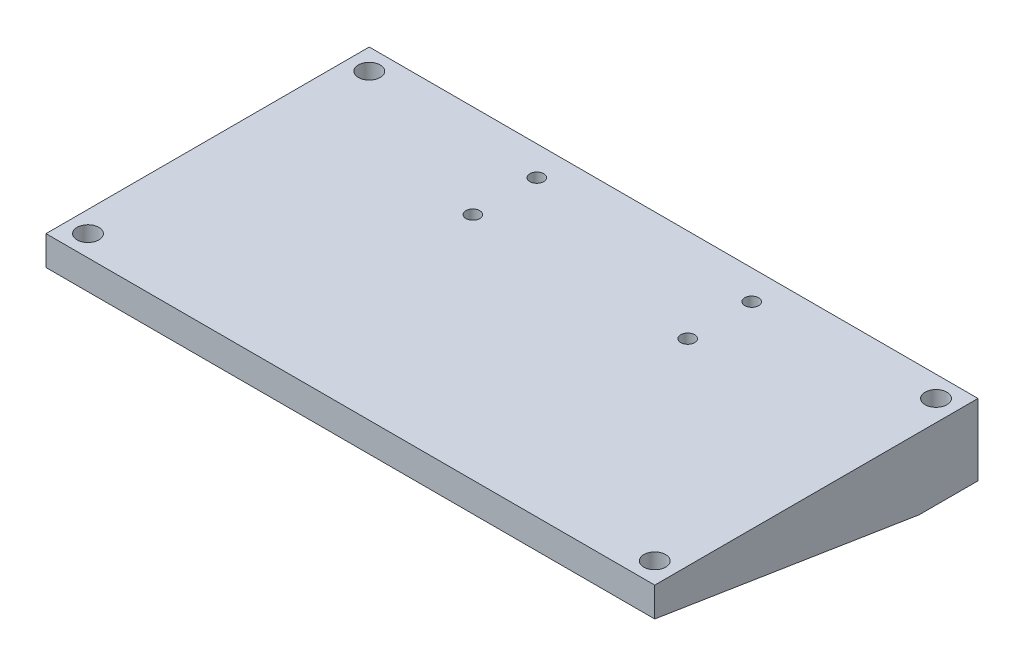
SolidWorks part; units mm, degrees
ref_plane "Front Plane" through (0, 0, 0) normal (0, 0, 1) x (1, 0, 0)
ref_plane "Top Plane" through (0, 0, 0) normal (0, 1, 0) x (1, 0, 0)
ref_plane "Right Plane" through (0, 0, 0) normal (1, 0, 0) x (0, 0, -1)
sketch "Sketch5" plane through (0, 0, 0) normal (0, 1, 0) x (1, 0, 0)
  line L5 (0, 0) -> (145, 0)
  line L6 (0, 0) -> (0, 77)
  line L7 (0, 77) -> (145, 77)
  line L8 (145, 0) -> (145, 77)
  dimension "D1" = 145
  dimension "D2" = 77
extrude "Boss-Extrude2" add sketch "Sketch5" along normal blind 17
chamfer "Chamfer2" distance 63 distance2 10 1 edges at (72.5, 0, 0)
sketch "Sketch1" plane through (0, 17, 0) normal (0, 1, 0) x (1, 0, 0)
  line L1 (0, 0) -> (145, 0)
  line L2 (0, 0) -> (0, 77)
  line L3 (0, 77) -> (145, 77)
  line L4 (145, 0) -> (145, 77)
  line L5 (50.91, 71.27) -> (94.09, 71.27)
  line L6 (50.91, 71.27) -> (50.91, 53.49)
  line L7 (50.91, 53.49) -> (94.09, 53.49)
  line L8 (94.09, 71.27) -> (94.09, 53.49)
  circle A0 centre (5, 72) radius 2.6
  circle A1 centre (5, 5) radius 2.6
  circle A2 centre (140, 5) radius 2.6
  circle A3 centre (140, 72) radius 2.6
  circle A4 centre (52.18, 70) radius 0.889
  circle A5 centre (52.18, 54.76) radius 0.889
  circle A6 centre (92.82, 54.76) radius 0.889
  circle A7 centre (92.82, 70) radius 0.889
  circle A8 centre (46.91, 70) radius 1.65
  circle A9 centre (46.91, 54.76) radius 1.65
  circle A10 centre (98.09, 70) radius 1.65
  circle A11 centre (98.09, 54.76) radius 1.65
  point P31 (0, 0)
  point P34 (0, 0)
  point P35 (0, 0)
  point P36 (0, 0)
  dimension "D1" = 5.2
  dimension "D2" = 5.2
  dimension "D3" = 5.2
  dimension "D12" = 5.2
  dimension "D27" = 1.778
  dimension "D28" = 1.778
  dimension "D29" = 1.778
  dimension "D30" = 1.778
  dimension "D32" = 3.3
  dimension "D33" = 3.3
  dimension "D35" = 3.3
  dimension "D36" = 3.3
  dimension "D4" = 5
  dimension "D5" = 5
  dimension "D6" = 5
  dimension "D7" = 5
  dimension "D8" = 5
  dimension "D9" = 5
  dimension "D10" = 5
  dimension "D11" = 5
  dimension "D13" = 145
  dimension "D14" = 77
  dimension "D15" = 17.78
  dimension "D16" = 43.18
  dimension "D17" = 7
  dimension "D18" = 50.91
  dimension "D19" = 1.27
  dimension "D20" = 1.27
  dimension "D21" = 1.27
  dimension "D22" = 1.27
  dimension "D23" = 1.27
  dimension "D24" = 1.27
  dimension "D25" = 1.27
  dimension "D26" = 1.27
  dimension "D31" = 4
  dimension "D34" = 4
  dimension "D37" = 4
  dimension "D38" = 4
extrude "Cut-Extrude1" cut sketch "Sketch1" against normal blind 5 contours A0 | A1 | A2 | A3 | A8 | A9 | A10 | A11
